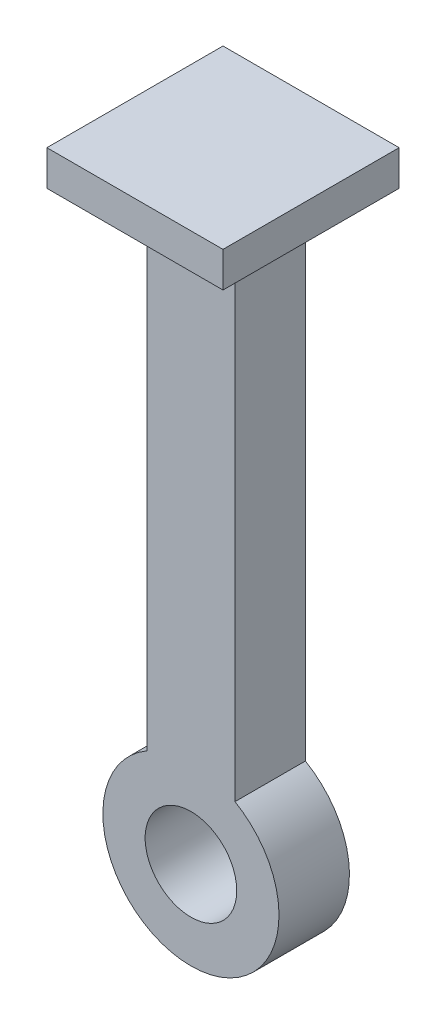
SolidWorks part; units mm, degrees
ref_plane "Front Plane" through (0, 0, 0) normal (0, 0, 1) x (1, 0, 0)
ref_plane "Top Plane" through (0, 0, 0) normal (0, 1, 0) x (1, 0, 0)
ref_plane "Right Plane" through (0, 0, 0) normal (1, 0, 0) x (0, 0, -1)
sketch "Sketch1" plane through (0, 0, 0) normal (0, 0, 1) x (1, 0, 0)
  line L0 (3.175, 5.4993) -> (3.175, 41.0593)
  line L3 (-3.175, 41.0593) -> (3.175, 41.0593)
  line L6 (-3.175, 41.0593) -> (-1.9825, 28.0228) construction
  line L8 (-1.9825, 28.0228) -> (3.175, 41.0593) construction
  line L9 (-3.175, 5.4993) -> (-3.175, 41.0593)
  circle A0 centre (0, 0) radius 3.302
  circle A1 centre (0, 0) radius 6.35
  point P4 (0, 6.35)
  dimension "D1" = 12.7
extrude "Boss-Extrude1" add sketch "Sketch1" along normal blind 5.08 contours A1 A0 | A1 L0 L3 L9
sketch "Sketch2" plane through (0, 41.0593, 0) normal (0, 1, 0) x (1, 0, 0)
  line L1 (-6.35, 3.5822) -> (6.35, 3.5822)
  line L2 (-6.35, 3.5822) -> (-6.35, -9.1178)
  line L3 (-6.35, -9.1178) -> (6.35, -9.1178)
  line L4 (6.35, 3.5822) -> (6.35, -9.1178)
  line L5 (-6.35, 3.5822) -> (6.35, -9.1178) construction
  line L6 (-6.35, -9.1178) -> (6.35, 3.5822) construction
  point P0 (0, -2.7678)
  point P5 (0.3645, -3.1453)
  point P6 (0, -2.7678)
extrude "Boss-Extrude2" add sketch "Sketch2" along normal blind 2.54
